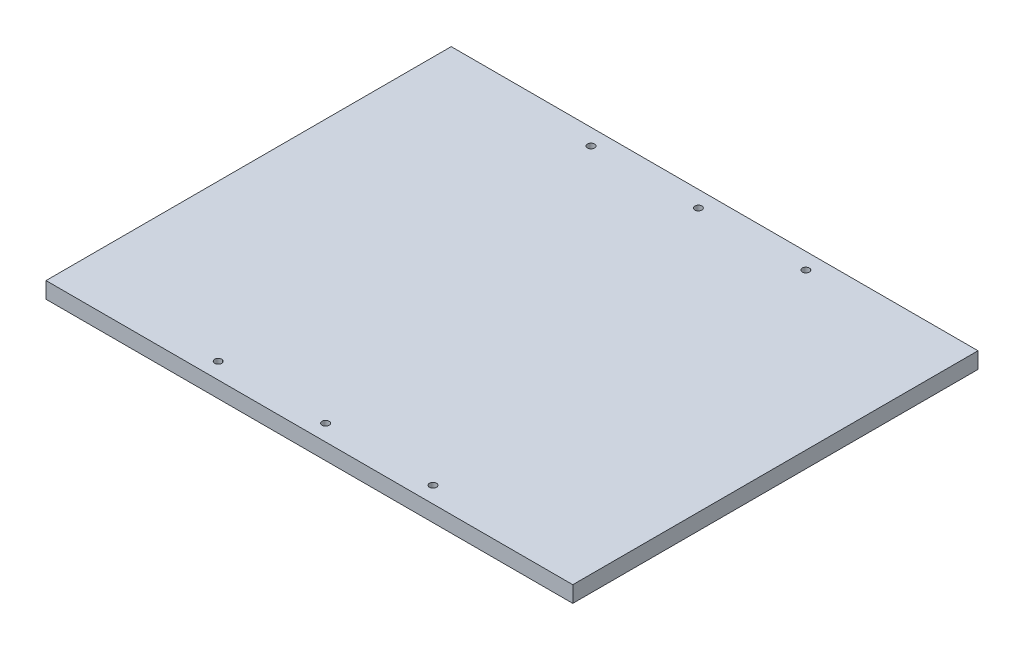
SolidWorks part; units mm, degrees
ref_plane "Ebene vorne" through (0, 0, 0) normal (0, 0, 1) x (1, 0, 0)
ref_plane "Ebene oben" through (0, 0, 0) normal (0, 1, 0) x (1, 0, 0)
ref_plane "Ebene rechts" through (0, 0, 0) normal (1, 0, 0) x (0, 0, -1)
sketch "Skizze1" plane through (0, 0, 0) normal (0, 1, 0) x (1, 0, 0)
  line L0 (-53, -92) -> (53, -92) construction
  line L1 (-130, -100) -> (130, -100)
  line L2 (-130, -100) -> (-130, 100)
  line L3 (-130, 100) -> (130, 100)
  line L4 (130, -100) -> (130, 100)
  line L5 (-130, -100) -> (130, 100) construction
  line L6 (-130, 100) -> (130, -100) construction
  line L7 (0, 0) -> (-130, 0) construction
  line L8 (130, 0) -> (0, 0) construction
  line L9 (0, 0) -> (0, 100) construction
  line L10 (0, 0) -> (0, -100) construction
  line L11 (-53, 92) -> (53, 92) construction
  circle A0 centre (-53, -92) radius 1.75
  circle A1 centre (53, -92) radius 1.75
  circle A2 centre (0, -92) radius 1.75
  circle A3 centre (0, 92) radius 1.75
  circle A4 centre (53, 92) radius 1.75
  circle A5 centre (-53, 92) radius 1.75
  point P0 (0, 0)
  dimension "D3" = 3.5
  dimension "D4" = 3.5
  dimension "D5" = 3.5
  dimension "D1" = 260
  dimension "D2" = 200
  dimension "D6" = 106
  dimension "D7" = 8
extrude "Aufsatz-Linear austragen1" add sketch "Skizze1" along normal blind 8
